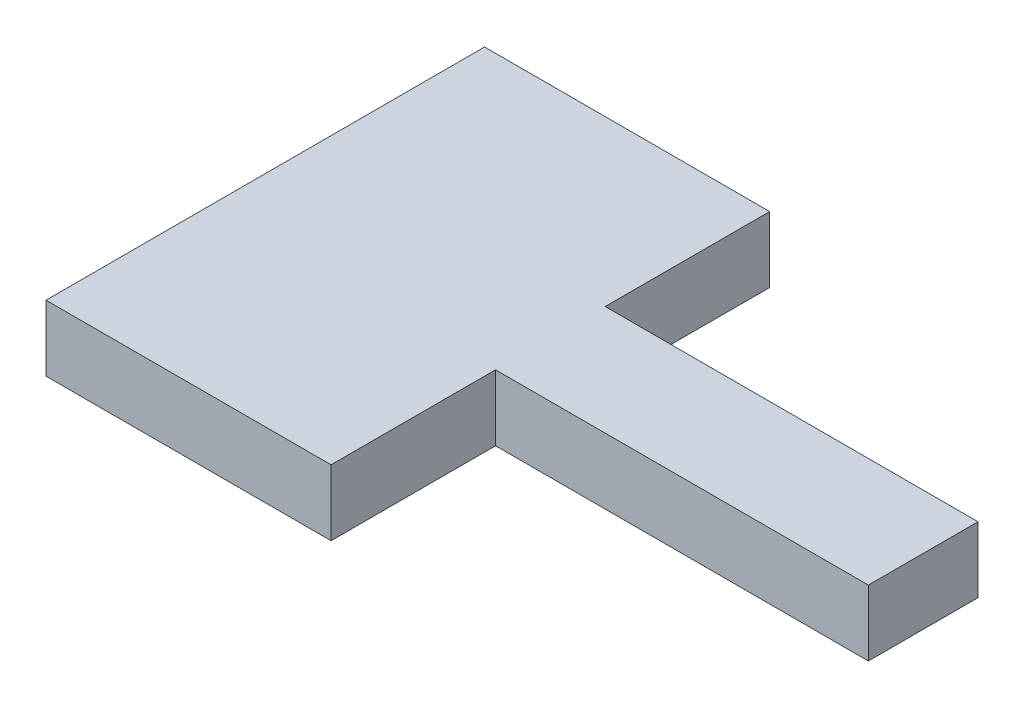
SolidWorks part; units mm, degrees
ref_plane "Front Plane" through (0, 0, 0) normal (0, 0, 1) x (1, 0, 0)
ref_plane "Top Plane" through (0, 0, 0) normal (0, 1, 0) x (1, 0, 0)
ref_plane "Right Plane" through (0, 0, 0) normal (1, 0, 0) x (0, 0, -1)
sketch "Sketch1" plane through (0, 0, 0) normal (0, 1, 0) x (1, 0, 0)
  line L0 (0, 0) -> (47.455, 0) construction
  line L1 (6.5, -10) -> (-6.5, -10)
  line L2 (6.5, -10) -> (6.5, -2.5)
  line L3 (6.5, 10) -> (-6.5, 10)
  line L4 (-6.5, -10) -> (-6.5, 10)
  line L5 (6.5, -10) -> (-6.5, 10) construction
  line L6 (6.5, 10) -> (-6.5, -10) construction
  line L7 (6.5, 2.5) -> (23.5, 2.5)
  line L9 (6.5, -2.5) -> (23.5, -2.5)
  line L10 (23.5, 2.5) -> (23.5, -2.5)
  line L11 (6.5, 2.5) -> (6.5, 10)
  point P0 (0, 0)
  dimension "D1" = 13
  dimension "D2" = 20
  dimension "D3" = 17
  dimension "D4" = 5
  dimension "D5" = 2.5
extrude "Boss-Extrude1" add sketch "Sketch1" along normal blind 3
